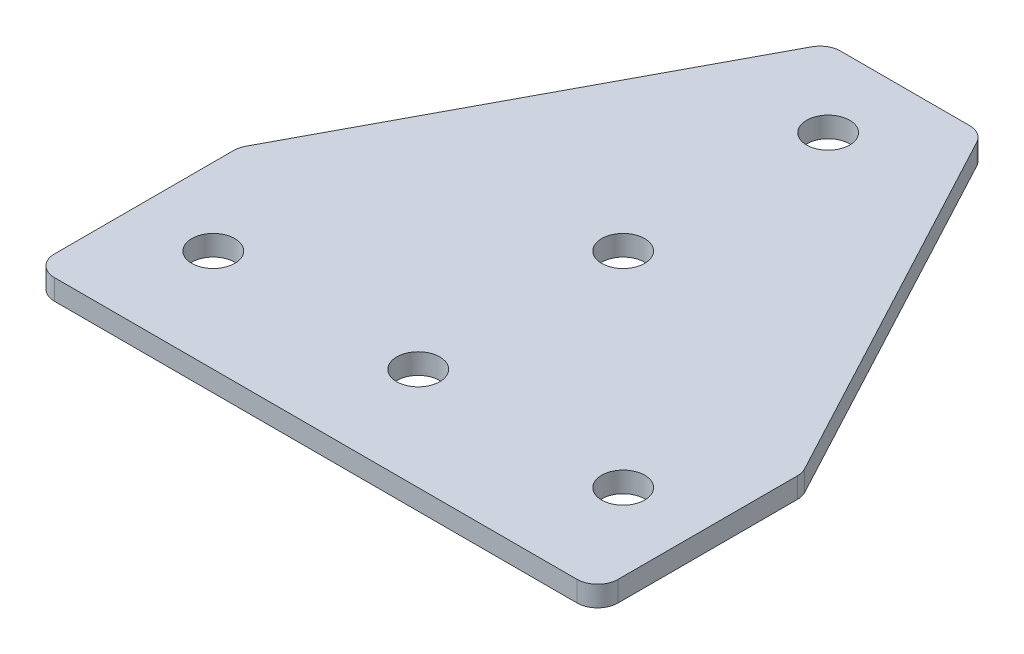
SolidWorks part; units mm, degrees
material "5052-H34"
ref_plane "正面" through (0, 0, 0) normal (0, 0, 1) x (1, 0, 0)
ref_plane "平面" through (0, 0, 0) normal (0, 1, 0) x (1, 0, 0)
ref_plane "右側面" through (0, 0, 0) normal (1, 0, 0) x (0, 0, -1)
sketch "ｽｹｯﾁ1" plane through (0, 0, 0) normal (0, 1, 0) x (1, 0, 0)
  line L0 (0, 0) -> (55, 0)
  line L1 (55, 0) -> (55, 20)
  line L2 (55, 20) -> (35, 57.5)
  line L3 (35, 57.5) -> (20, 57.5)
  line L4 (20, 57.5) -> (0, 20)
  line L5 (0, 20) -> (0, 0)
  line L6 (27.5, 0) -> (27.5, 57.5) construction
  line L7 (55, 10) -> (0, 10) construction
  circle A0 centre (7.5, 10) radius 2.1
  circle A1 centre (47.5, 10) radius 2.1
  circle A2 centre (27.5, 10) radius 2.1
  circle A3 centre (27.5, 50) radius 2.1
  circle A6 centre (27.5, 30) radius 2.1
  dimension "D3" = 4.2
  dimension "D4" = 7.5
  dimension "D5" = 7.5
  dimension "D6" = 10
  dimension "D7" = 20
  dimension "D9" = 20
  dimension "D1" = 20
  dimension "D2" = 15
extrude "ﾎﾞｽ - 押し出し1" add sketch "ｽｹｯﾁ1" along normal blind 2
fillet "ﾌｨﾚｯﾄ1" radius 2 6 edges at (0, 1, -20) (0, 1, 0) (55, 1, 0) (55, 1, -20) (35, 1, -57.5) (20, 1, -57.5)
